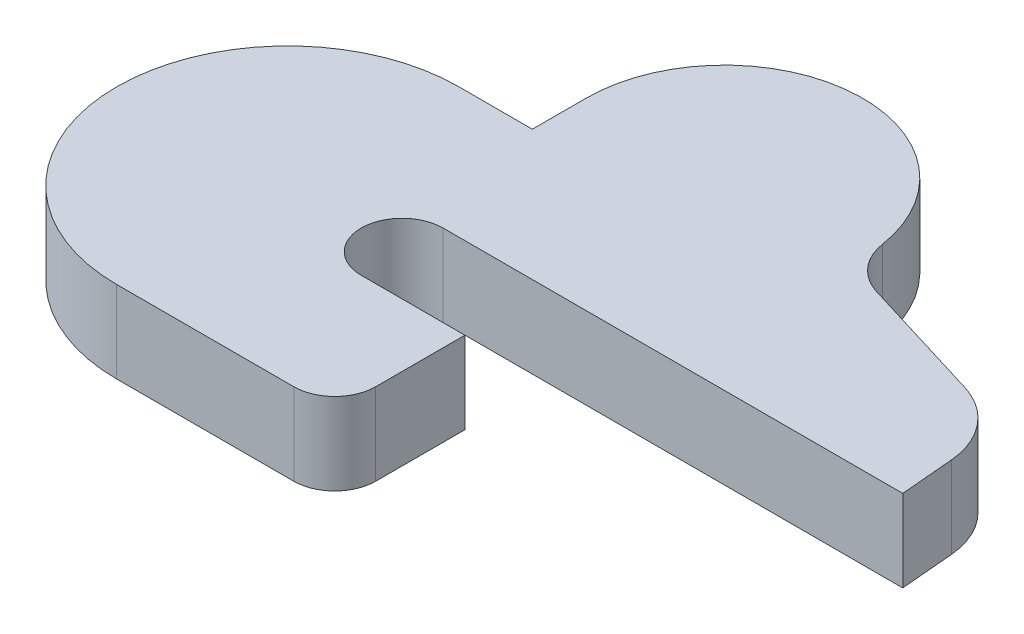
SolidWorks part; units mm, degrees
ref_plane "Front Plane" through (0, 0, 0) normal (0, 0, 1) x (1, 0, 0)
ref_plane "Top Plane" through (0, 0, 0) normal (0, 1, 0) x (1, 0, 0)
ref_plane "Right Plane" through (0, 0, 0) normal (1, 0, 0) x (0, 0, -1)
sketch "Sketch1" plane through (0, 0, 0) normal (0, 1, 0) x (1, 0, 0)
  line L0 (0, 0) -> (-3.8, 0)
  line L1 (-3.8, 3) -> (13.04, 3)
  line L2 (13.04, 3) -> (12.8683, 4.9631)
  line L6 (-5.3, 9.7421) -> (-5.3, 7.77)
  line L7 (-5.3, 7.77) -> (-7.99, 7.77)
  line L9 (0, -3.27) -> (0, 0)
  line L10 (-7.99, -4.77) -> (-1.5, -4.77)
  line L11 (6.1563, 8.924) -> (10.8139, 7.5)
  arc A0 (-3.8, 0) -> (-3.8, 3) centre (-3.8, 1.5) cw
  arc A1 (12.8683, 4.9631) -> (10.8139, 7.5) centre (9.9605, 4.7087) ccw
  arc A5 (-7.99, 7.77) -> (-7.99, -4.77) centre (-7.99, 1.5) ccw
  arc A10 (-1.5, -4.77) -> (0, -3.27) centre (-1.5, -3.27) ccw
  arc A11 (-5.3, 9.7421) -> (4.7652, 10.5267) centre (-0.2368, 9.7421) cw
  arc A12 (4.7652, 10.5267) -> (6.1563, 8.924) centre (6.741, 10.8366) ccw
  point P10 (-0.6303, 14.79)
  point P12 (-14.26, 1.5)
  point P15 (4.81, 9.3356)
  point P44 (-5.3, 1.5)
  dimension "10.9" = 6.27
  dimension "D4" = 1.5
  dimension "D5" = 19.56
  dimension "D6" = 17
  dimension "D7" = 2
  dimension "D11" = 1.5
  dimension "D2" = 5.0632
  dimension "D3" = 27.3
  dimension "3.65" = 4.5
  dimension "80" = 85
  dimension "D8" = 16.84
  dimension "D9" = 3.8
  dimension "5" = 8.23
extrude "Boss-Extrude2" add sketch "Sketch1" along normal blind 3
